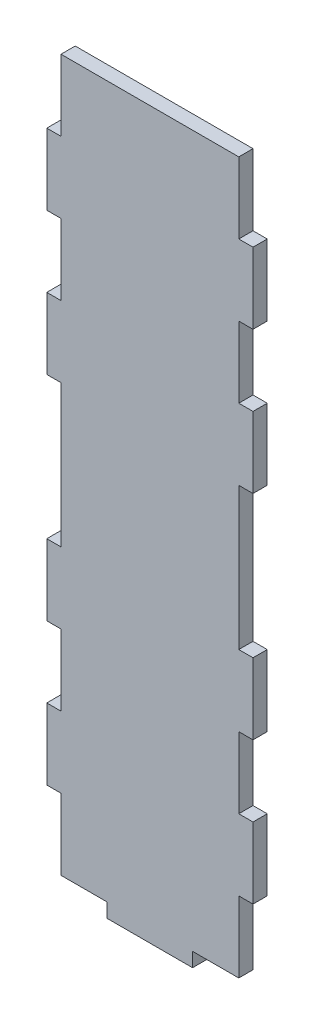
SolidWorks part; units mm, degrees
ref_plane "Plano frontal" through (0, 0, 0) normal (0, 0, 1) x (1, 0, 0)
ref_plane "Plano superior" through (0, 0, 0) normal (0, 1, 0) x (1, 0, 0)
ref_plane "Plano direito" through (0, 0, 0) normal (1, 0, 0) x (0, 0, -1)
sketch "Esboço1" plane through (0, 0, 0) normal (0, 0, 1) x (1, 0, 0)
  line L0 (0, 100) -> (0, -100) construction
  line L1 (-50, -100) -> (-37, -100)
  line L2 (-50, -100) -> (-50, 100)
  line L3 (-50, 100) -> (50, 100)
  line L4 (50, -100) -> (50, 100)
  line L5 (-50, -100) -> (50, 100) construction
  line L6 (-50, 100) -> (50, -100) construction
  line L7 (-50, 0) -> (50, 0) construction
  line L8 (-37, -100) -> (-37, -104)
  line L9 (-37, -104) -> (-13, -104)
  line L10 (-13, -104) -> (-13, -100)
  line L11 (13, -104) -> (13, -100)
  line L12 (37, -104) -> (13, -104)
  line L13 (37, -100) -> (37, -104)
  line L14 (-13, -100) -> (13, -100)
  line L15 (37, -100) -> (50, -100)
  point P0 (0, 0)
  dimension "D1" = 100
  dimension "D2" = 200
  dimension "D3" = 4
  dimension "D4" = 24
  dimension "D5" = 13
extrude "Ressalto-extrusão1" add sketch "Esboço1" along normal blind 4
sketch "Esboço2" plane through (0, 0, 4) normal (0, 0, 1) x (1, 0, 0)
  line L0 (0, -100) -> (0, 100)
  line L1 (-13, -100) -> (13, -100) construction
  line L2 (50, 100) -> (-50, 100) construction
  line L3 (0, 80) -> (4, 80)
  line L4 (4, 80) -> (4, 60)
  line L5 (4, 60) -> (0, 60)
  line L6 (-50, 0) -> (50, 0) construction
  line L7 (-50, 100) -> (-50, -100) construction
  line L8 (50, -100) -> (50, 100) construction
  line L9 (0, 40) -> (4, 40)
  line L10 (4, 40) -> (4, 20)
  line L11 (4, 20) -> (0, 20)
  line L12 (0, 40) -> (0, 20)
  line L13 (0, 80) -> (0, 60)
  line L14 (0, -80) -> (4, -80)
  line L15 (4, -80) -> (4, -60)
  line L16 (4, -60) -> (0, -60)
  line L17 (0, -80) -> (0, -60)
  line L18 (0, -40) -> (4, -40)
  line L19 (4, -40) -> (4, -20)
  line L20 (4, -20) -> (0, -20)
  line L21 (0, -40) -> (0, -20)
  line M10 (50, -100) -> (50, 100)
  line M11 (50, 100) -> (-50, 100)
  line M17 (-13, -100) -> (13, -100)
  line M18 (13, -100) -> (13, -104)
  line M19 (13, -104) -> (37, -104)
  line M20 (37, -104) -> (37, -100)
  line M21 (37, -100) -> (50, -100)
  dimension "D1" = 4
  dimension "D2" = 20
  dimension "D3" = 20
  dimension "D4" = 20
extrude "Corte-extrusão3" cut sketch "Esboço2" against normal through all contours L0 L6 L3 L4 L5 L9 L10 L11 M10 M11 | L6 L0 L20 L19 L18 L16 L15 L14 M17 M18 M19 M20 M21 M10
sketch "Esboço4" plane through (0, 0, 4) normal (0, 0, 1) x (1, 0, 0)
  line L0 (-50, 80) -> (-54, 80)
  line L1 (-50, 100) -> (-50, -100) construction
  line L2 (-54, 80) -> (-54, 60)
  line L3 (-54, 60) -> (-50, 60)
  line L4 (-50, 40) -> (-54, 40)
  line L5 (-54, 40) -> (-54, 20)
  line L6 (-54, 20) -> (-50, 20)
  line L7 (0, 0) -> (-50, 0) construction
  line L8 (-50, 80) -> (-50, 60)
  line L9 (-50, 40) -> (-50, 20)
  line L10 (0, 100) -> (-50, 100) construction
  line L11 (-50, -80) -> (-54, -80)
  line L12 (-54, -80) -> (-54, -60)
  line L13 (-54, -60) -> (-50, -60)
  line L14 (-50, -80) -> (-50, -60)
  line L15 (-50, -40) -> (-54, -40)
  line L16 (-54, -40) -> (-54, -20)
  line L17 (-54, -20) -> (-50, -20)
  line L18 (-50, -40) -> (-50, -20)
  dimension "D1" = 4
  dimension "D2" = 20
  dimension "D3" = 20
  dimension "D4" = 20
extrude "Ressalto-extrusão2" add sketch "Esboço4" against normal blind 4
